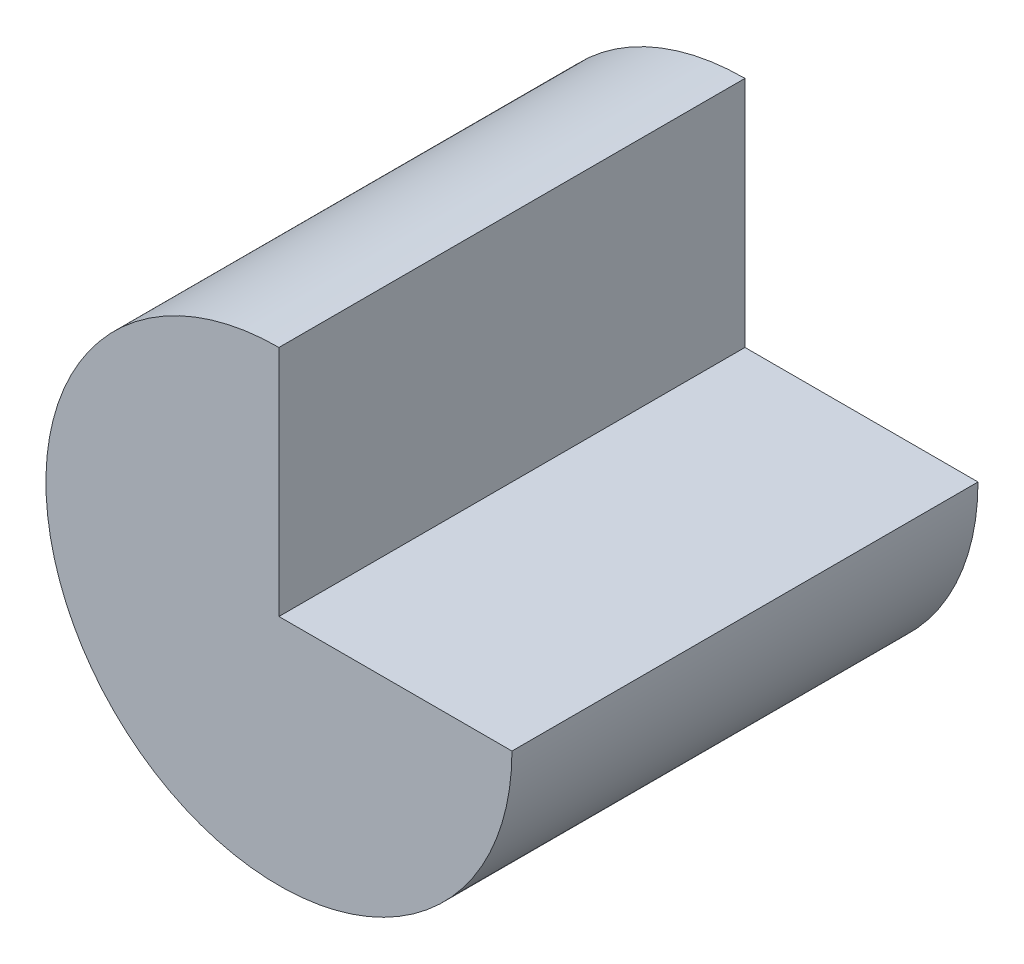
SolidWorks part; units mm, degrees
ref_plane "Front Plane" through (0, 0, 0) normal (0, 0, 1) x (1, 0, 0)
ref_plane "Top Plane" through (0, 0, 0) normal (0, 1, 0) x (1, 0, 0)
ref_plane "Right Plane" through (0, 0, 0) normal (1, 0, 0) x (0, 0, -1)
sketch "Sketch1" plane through (0, 0, 0) normal (0, 0, 1) x (1, 0, 0)
  line L0 (0, 76.2) -> (0, 0)
  line L1 (0, 0) -> (76.2, 0)
  arc A0 (0, 76.2) -> (76.2, 0) centre (0, 0) ccw
  dimension "D1" = 76.2
extrude "Boss-Extrude1" add sketch "Sketch1" against normal blind 152.4
